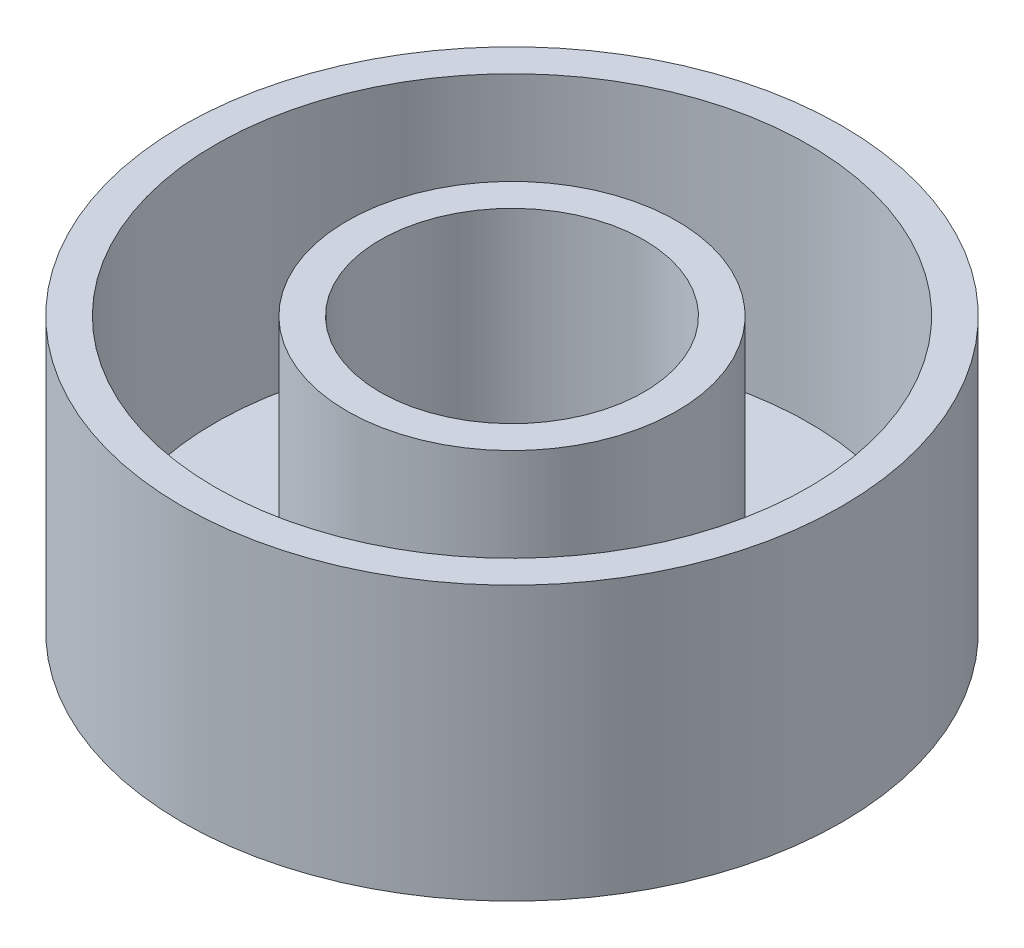
SolidWorks part; units mm, degrees
material "VITON"
ref_plane "Front Plane" through (0, 0, 0) normal (0, 0, 1) x (1, 0, 0)
ref_plane "Top Plane" through (0, 0, 0) normal (0, 1, 0) x (1, 0, 0)
ref_plane "Right Plane" through (0, 0, 0) normal (1, 0, 0) x (0, 0, -1)
sketch "Sketch1" plane through (0, 0, 0) normal (0, 1, 0) x (1, 0, 0)
  circle A0 centre (0, 0) radius 10
  dimension "D1" = 20
extrude "main extrusion" add sketch "Sketch1" along normal blind 8.3 contours A0
sketch "Sketch2" plane through (0, 8.3, 0) normal (0, 1, 0) x (1, 0, 0)
  circle A0 centre (0, 0) radius 4
  dimension "D1" = 8
extrude "ID bore" cut sketch "Sketch2" against normal blind 20
sketch "Sketch3" plane through (0, 8.3, 0) normal (0, 1, 0) x (1, 0, 0)
  circle A0 centre (0, 0) radius 9
  circle A1 centre (0, 0) radius 5
  dimension "D1" = 10
  dimension "D2" = 18
extrude "seal recess" cut sketch "Sketch3" against normal blind 7.3
equation "\"D1@Sketch1\" = \"small seal OD\""
equation "\"D1@main extrusion\" = \"small seal depth\""
equation "\"D1@Sketch2\"= \"small seal ID\""
equation "\"motor mount pattern diameter\"= 30mm"
equation "\"D2@Sketch3\" = \"small seal OD\" - 2mm"
equation "\"D1@Sketch3\" = \"small seal ID\" + 2mm"
equation "\"D1@seal recess\" = \"small seal depth\" - 1mm"
equation "\"bearing OD\" = 30mm"
equation "\"bearing outer race thickness\"= 1mm"
equation "\"bearing ID\"= 10mm"
equation "\"bearing depth\"= 9mm"
equation "\"bearing inner race thickness\"= 1mm"
equation "\"small seal OD\" = 20mm"
equation "\"small seal ID\"= 8mm"
equation "\"small seal depth\" = 8.3mm"
equation "\"big seal OD\" = 27mm"
